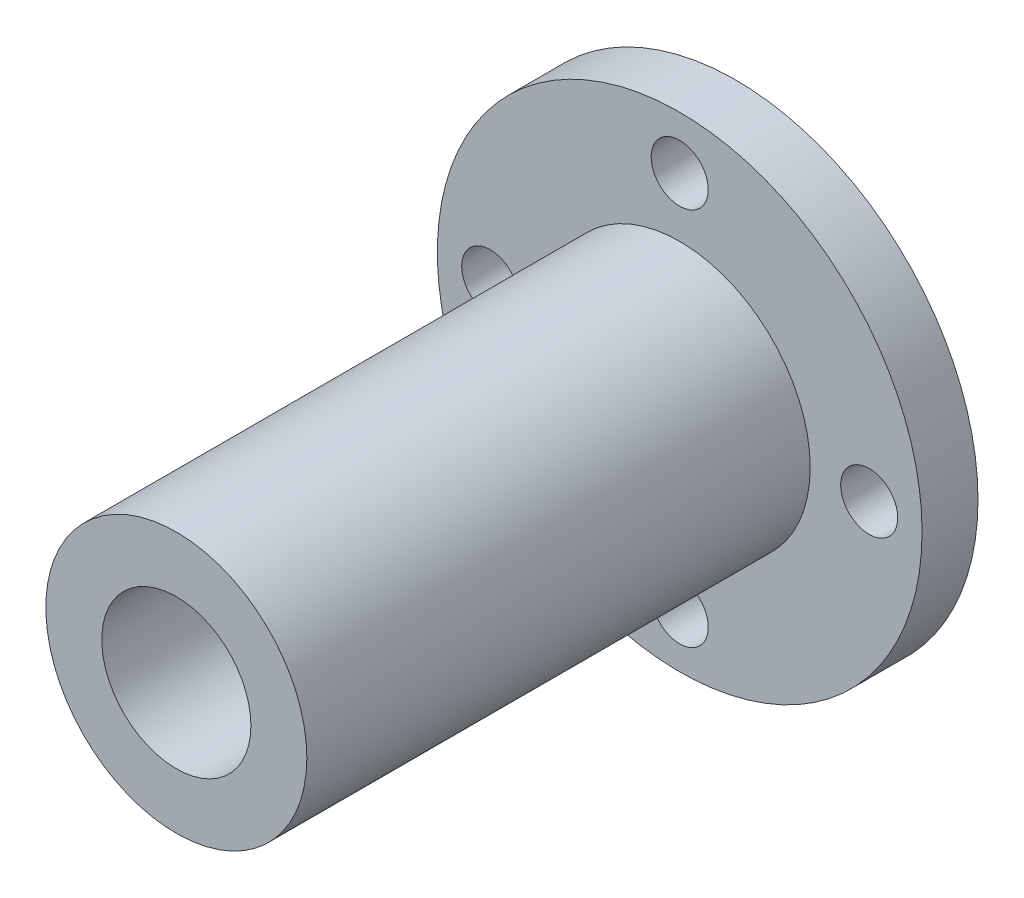
SolidWorks part; units mm, degrees
material "Bronce comercial al plomo"
ref_plane "Alzado" through (0, 0, 0) normal (0, 0, 1) x (1, 0, 0)
ref_plane "Planta" through (0, 0, 0) normal (0, 1, 0) x (1, 0, 0)
ref_plane "Vista lateral" through (0, 0, 0) normal (1, 0, 0) x (0, 0, -1)
sketch "Croquis1" plane through (0, 0, 0) normal (1, 0, 0) x (0, 0, -1)
  line L0 (0, 0) -> (0, 9)
  line L1 (0, 9) -> (-3, 9)
  line L2 (-3, 9) -> (-3, 3)
  line L3 (-3, 3) -> (-30, 3)
  line L4 (0, 0) -> (-30, 0)
  line L5 (-30, 0) -> (-30, 3)
  line L6 (-49.0462, -4) -> (0, -4) construction
  dimension "D1" = 4
  dimension "D2" = 3
  dimension "D3" = 30
  dimension "D4" = 6
  dimension "D5" = 3
revolve "Revolución1" add sketch "Croquis1" angle 360 about L6
sketch "Croquis2" plane through (0, 0, 0) normal (0, 0, -1) x (-1, 0, 0)
  circle A0 centre (0, 6.1638) radius 1.5309
  circle A1 centre (10.1638, -4) radius 1.5309
  circle A2 centre (0, -14.1638) radius 1.5309
  circle A3 centre (-10.1638, -4) radius 1.5309
  point P11 (0, -4)
  dimension "D1" = 4
extrude "Cortar-Extruir1" cut sketch "Croquis2" against normal blind 10
